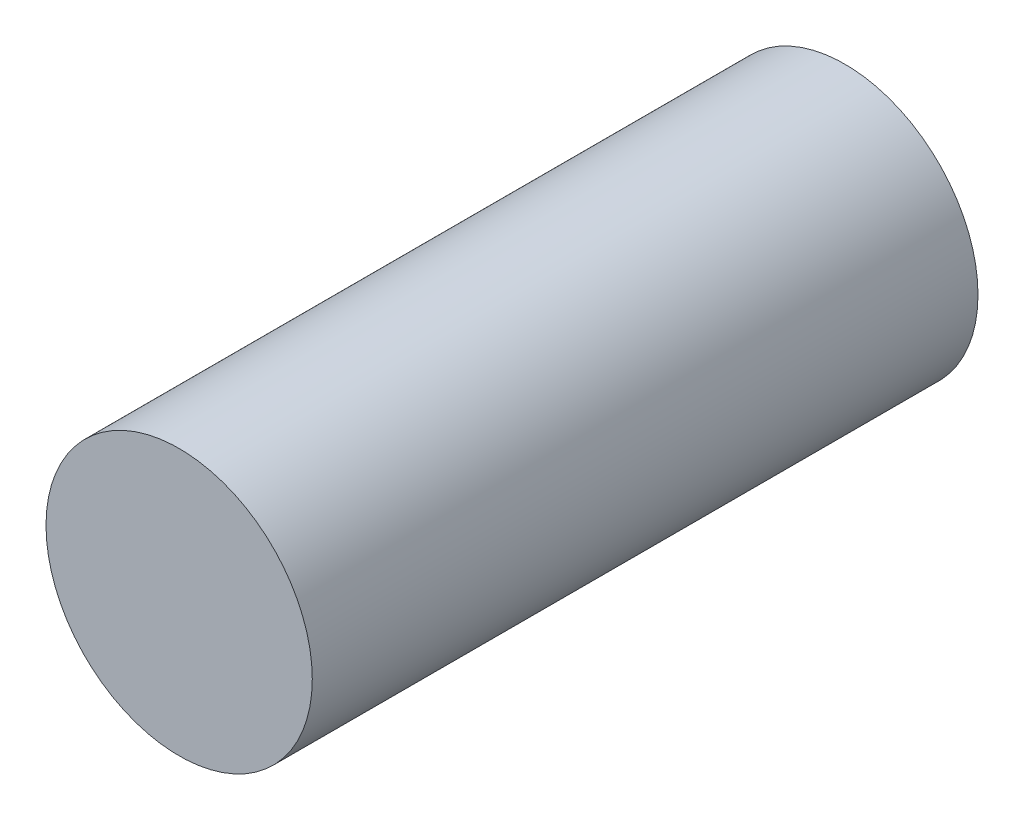
SolidWorks part; units mm, degrees
ref_plane "Front Plane" through (0, 0, 0) normal (0, 0, 1) x (1, 0, 0)
ref_plane "Top Plane" through (0, 0, 0) normal (0, 1, 0) x (1, 0, 0)
ref_plane "Right Plane" through (0, 0, 0) normal (1, 0, 0) x (0, 0, -1)
sketch "Sketch1" plane through (0, 0, 0) normal (0, 0, 1) x (1, 0, 0)
  circle A0 centre (0, 0) radius 0.5
  dimension "D1" = 1
extrude "Boss-Extrude1" add sketch "Sketch1" along normal blind 2.5
